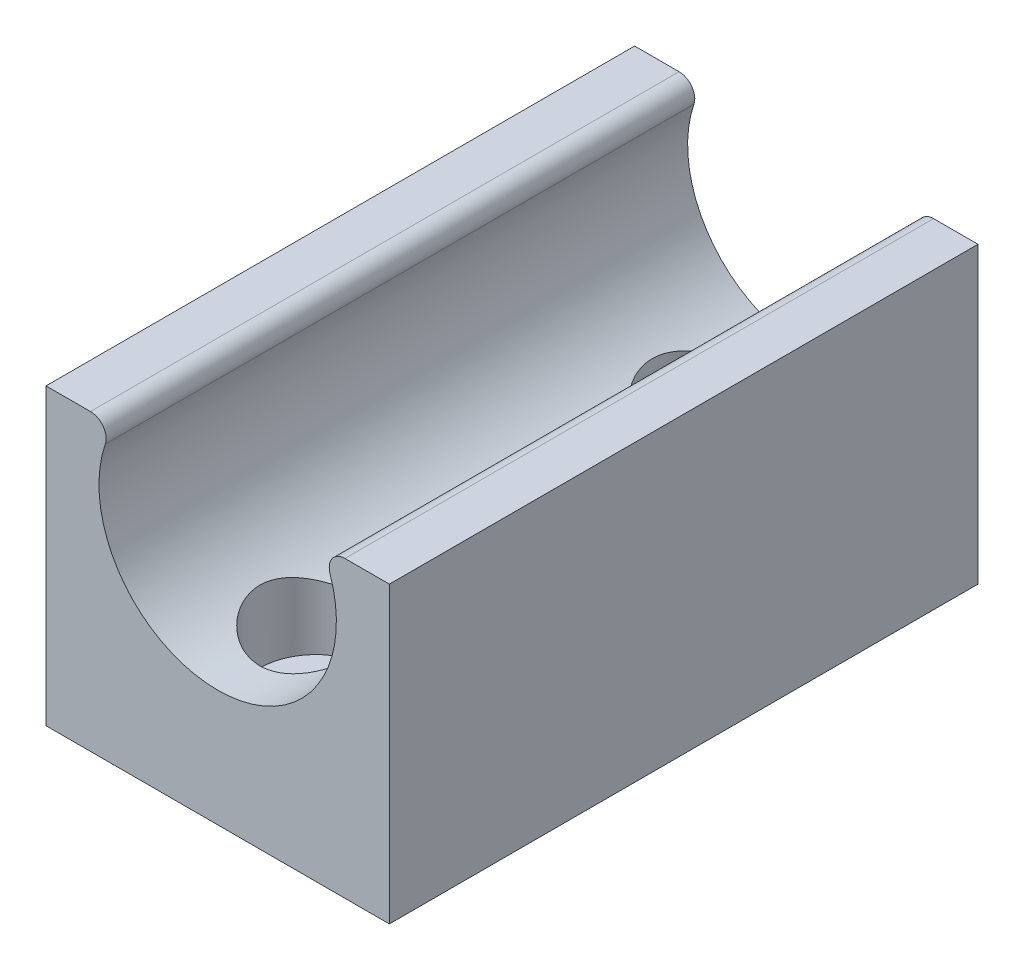
SolidWorks part; units mm, degrees
ref_plane "Front Plane" through (0, 0, 0) normal (0, 0, 1) x (1, 0, 0)
ref_plane "Top Plane" through (0, 0, 0) normal (0, 1, 0) x (1, 0, 0)
ref_plane "Right Plane" through (0, 0, 0) normal (1, 0, 0) x (0, 0, -1)
sketch "Sketch1" plane through (0, 0, 0) normal (0, 0, 1) x (1, 0, 0)
  line L0 (-5.25, 7.5) -> (-8.75, 7.5)
  line L1 (8.75, -7.5) -> (-8.75, -7.5)
  line L2 (8.75, -7.5) -> (8.75, 7.5)
  line L3 (8.75, 7.5) -> (5.25, 7.5)
  line L4 (-8.75, -7.5) -> (-8.75, 7.5)
  line L5 (8.75, -7.5) -> (-8.75, 7.5) construction
  line L6 (8.75, 7.5) -> (-8.75, -7.5) construction
  arc A0 (-5.25, 7.5) -> (5.25, 7.5) centre (0, 4.4933) ccw
  point P0 (0, 0)
  dimension "D1" = 12.1
  dimension "D2" = 3.5
  dimension "D3" = 17.5
  dimension "D4" = 15
extrude "Boss-Extrude1" add sketch "Sketch1" along normal blind 30
fillet "Fillet1" radius 0.8 2 edges at (5.25, 7.5, 15) (-5.25, 7.5, 15)
sketch "Sketch3" plane through (0, 7.5, 0) normal (0, 1, 0) x (1, 0, 0)
  line L0 (6.05, 0) -> (-6.05, 0) construction
  line L1 (-6.05, -30) -> (6.05, -30) construction
  circle A0 centre (0, -5) radius 2.85
  circle A1 centre (0, -25) radius 2.85
  dimension "D1" = 5.7
  dimension "D2" = 5
  dimension "D3" = 5
extrude "Cut-Extrude1" cut sketch "Sketch3" against normal blind 12
sketch "Sketch4" plane through (0, 7.5, 0) normal (0, 1, 0) x (1, 0, 0)
  circle A0 centre (0, -5) radius 1.55
  circle A1 centre (0, -25) radius 1.55
  dimension "D1" = 3.1
  dimension "D2" = 3.1
extrude "Cut-Extrude2" cut sketch "Sketch4" against normal through all
